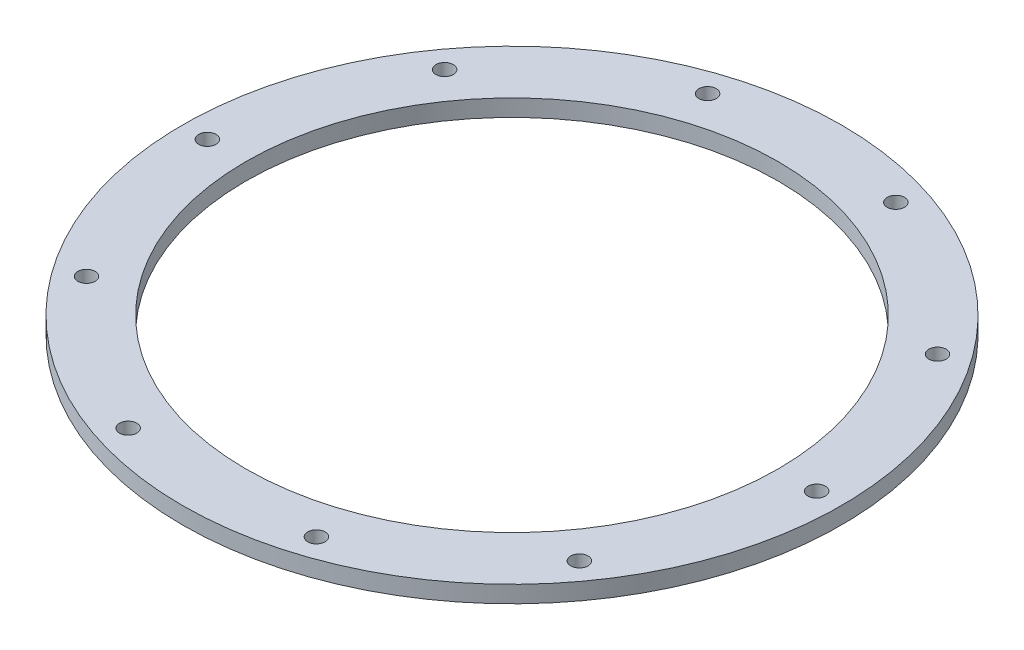
SolidWorks part; units mm, degrees
material "1060 合金"
ref_plane "前视基准面" through (0, 0, 0) normal (0, 0, 1) x (1, 0, 0)
ref_plane "上视基准面" through (0, 0, 0) normal (0, 1, 0) x (1, 0, 0)
ref_plane "右视基准面" through (0, 0, 0) normal (1, 0, 0) x (0, 0, -1)
sketch "草图1" plane through (0, 0, 0) normal (0, 1, 0) x (1, 0, 0)
  circle A0 centre (0, 0) radius 63
  circle A1 centre (0, 0) radius 78
  dimension "D1" = 126
  dimension "D2" = 15
extrude "凸台-拉伸1" add sketch "草图1" along normal blind 4
sketch "草图2" plane through (0, 4, 0) normal (0, 1, 0) x (1, 0, 0)
  circle A0 centre (0, 0) radius 72.1
  circle A1 centre (0, 0) radius 63 construction
  circle A2 centre (-72.1, 0) radius 2.05
  dimension "D1" = 9.1
  dimension "D2" = 4.1
extrude "切除-拉伸1" cut sketch "草图2" against normal blind 4 contours A0 A2 | A0 A2
pattern_circular "阵列(圆周)1" count 10 over 360 about axis through (0, 0, 0) along (0, 1, 0) of "切除-拉伸1"
